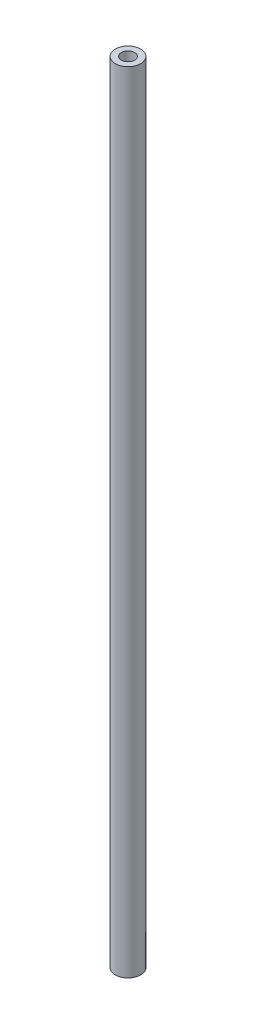
SolidWorks part; units mm, degrees
ref_plane "Front Plane" through (0, 0, 0) normal (0, 0, 1) x (1, 0, 0)
ref_plane "Top Plane" through (0, 0, 0) normal (0, 1, 0) x (1, 0, 0)
ref_plane "Right Plane" through (0, 0, 0) normal (1, 0, 0) x (0, 0, -1)
sketch "Sketch1" plane through (0, 0, 0) normal (0, 1, 0) x (1, 0, 0)
  circle A0 centre (0, 0) radius 0.3207
  circle A1 centre (0, 0) radius 0.1685
extrude "Boss-Extrude1" add sketch "Sketch1" along normal blind 20
